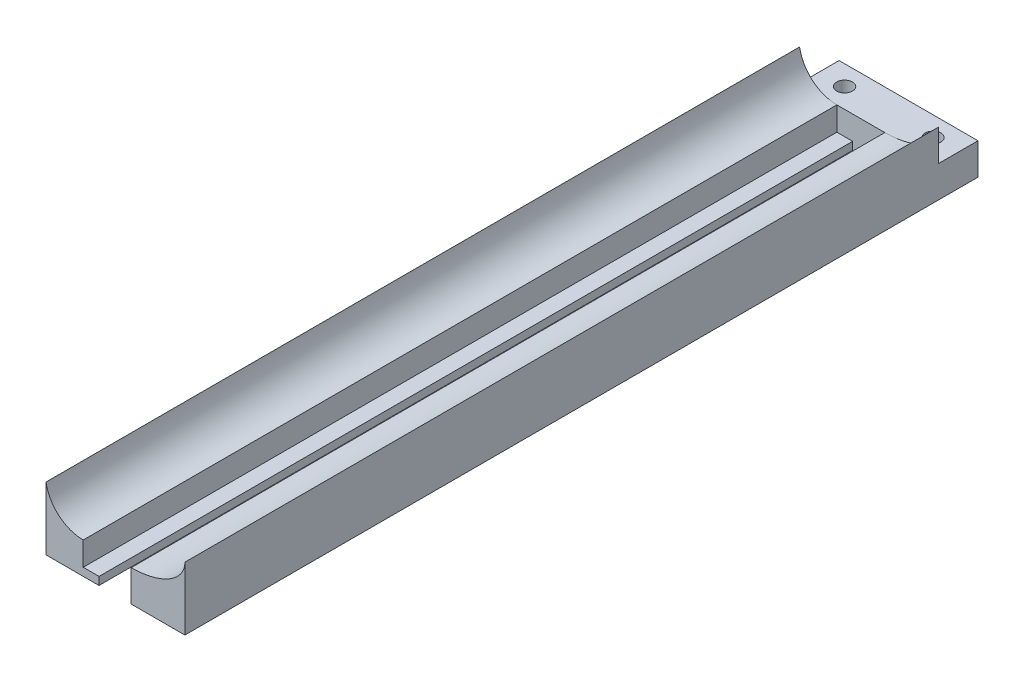
SolidWorks part; units mm, degrees
ref_plane "Front Plane" through (0, 0, 0) normal (0, 0, 1) x (1, 0, 0)
ref_plane "Top Plane" through (0, 0, 0) normal (0, 1, 0) x (1, 0, 0)
ref_plane "Right Plane" through (0, 0, 0) normal (1, 0, 0) x (0, 0, -1)
sketch "Sketch1" plane through (0, 0, 0) normal (0, 0, 1) x (1, 0, 0)
  line L1 (-13.97, -3.175) -> (13.97, -3.175)
  line L2 (-13.97, -3.175) -> (-13.97, 3.175)
  line L3 (-13.97, 3.175) -> (13.97, 3.175)
  line L4 (13.97, -3.175) -> (13.97, 3.175)
  line L5 (-13.97, -3.175) -> (13.97, 3.175) construction
  line L6 (-13.97, 3.175) -> (13.97, -3.175) construction
  point P0 (0, 0)
  dimension "D1" = 27.94
  dimension "D2" = 6.35
extrude "Boss-Extrude1" add sketch "Sketch1" along normal blind 7.9502
sketch "Sketch2" plane through (0, 0, 7.9502) normal (0, 0, 1) x (1, 0, 0)
  line L0 (-3.302, -3.175) -> (-3.302, -1.5875)
  line L1 (-13.97, -3.175) -> (13.97, -3.175) construction
  line L2 (-3.302, -1.5875) -> (-6.477, -1.5875)
  line L3 (-6.477, -1.5875) -> (-6.477, 3.175)
  line L4 (13.97, 3.175) -> (-13.97, 3.175) construction
  line L5 (-6.477, 3.175) -> (-13.97, 3.175)
  line L6 (-13.97, 3.175) -> (-13.97, -3.175)
  line L7 (-13.97, -3.175) -> (-3.302, -3.175)
  line L9 (13.97, -3.175) -> (3.175, -3.175)
  line L10 (13.97, -3.175) -> (13.97, 3.175)
  line L11 (13.97, 3.175) -> (3.175, 3.175)
  line L12 (3.175, -3.175) -> (3.175, 3.175)
  dimension "D1" = 1.5875
  dimension "D2" = 3.302
  dimension "D3" = 3.175
  dimension "D4" = 3.175
extrude "Boss-Extrude2" add sketch "Sketch2" along normal blind 151.6062
sketch "Sketch4" plane through (0, 3.175, 0) normal (0, 1, 0) x (1, 0, 0)
  line L0 (13.97, 0) -> (-13.97, 0) construction
  line L1 (-13.97, -159.5564) -> (-13.97, 0) construction
  line L2 (13.97, -159.5564) -> (13.97, 0) construction
  circle A0 centre (-8.89, -3.9751) radius 1.5875
  circle A1 centre (8.89, -3.9751) radius 1.5875
  dimension "D1" = 3.175
  dimension "D2" = 3.9751
  dimension "D3" = 3.9751
  dimension "D4" = 5.08
  dimension "D5" = 5.08
extrude "Cut-Extrude1" cut sketch "Sketch4" against normal through all
sketch "Sketch5" plane through (0, 0, 159.5564) normal (0, 0, 1) x (1, 0, 0)
  line L0 (-13.97, 3.175) -> (-13.97, 9.525)
  line L1 (-13.97, 3.175) -> (-6.477, 3.175)
  line L2 (3.175, 3.175) -> (13.97, 3.175)
  line L3 (13.97, 3.175) -> (13.97, 9.525)
  arc A1 (-6.477, 3.175) -> (-13.97, 9.525) centre (-6.477, 10.7709) cw
  ellipse E0 centre (3.175, 9.525) end of major axis (13.97, 9.525) minor radius 6.35 (3.175, 3.175) -> (13.97, 9.525) ccw
  dimension "D1" = 6.35
  dimension "D2" = 6.35
  dimension "D3" = 6.35
  dimension "D4" = 10.795
extrude "Boss-Extrude3" add sketch "Sketch5" against normal up to surface (151.6062 mm away) up to face at (-2.2013, -0.5292, 7.9502)
